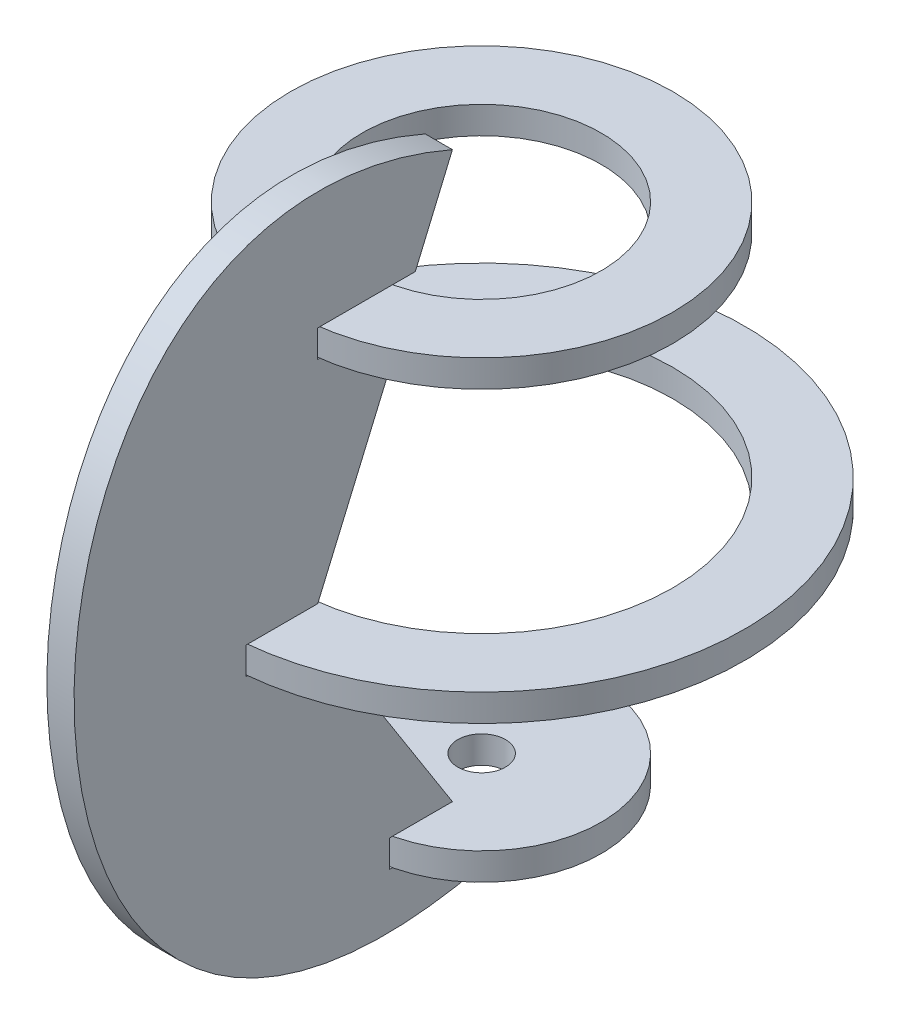
SolidWorks part; units mm, degrees
ref_plane "Piano frontale" through (0, 0, 0) normal (0, 0, 1) x (1, 0, 0)
ref_plane "Piano superiore" through (0, 0, 0) normal (0, 1, 0) x (1, 0, 0)
ref_plane "Piano destro" through (0, 0, 0) normal (1, 0, 0) x (0, 0, -1)
sketch "Schizzo2" plane through (0, 0, 0) normal (0, 1, 0) x (1, 0, 0)
  circle A0 centre (0, 0) radius 25.0225
  circle A1 centre (0, 0) radius 5
  dimension "D1" = 10
  dimension "D2" = 50.045
extrude "Estrusione-Estrusione1" add sketch "Schizzo2" along normal blind 5.7
ref_plane "Piano1" through (0, 50, 0) normal (0, 1, 0) x (1, 0, 0)
sketch "Schizzo3" plane through (0, 50, 0) normal (0, 1, 0) x (1, 0, 0)
  circle A0 centre (0, 0) radius 55.0225
  circle A1 centre (0, 0) radius 40.0225
  dimension "D1" = 110.045
  dimension "D2" = 80.045
extrude "Estrusione-Estrusione2" add sketch "Schizzo3" along normal blind 5.7 separate body
ref_plane "Piano2" through (0, 100, 0) normal (0, 1, 0) x (1, 0, 0)
sketch "Schizzo4" plane through (0, 100, 0) normal (0, 1, 0) x (1, 0, 0)
  circle A0 centre (0, 0) radius 40.0225
  circle A1 centre (0, 0) radius 25.0225
  dimension "D2" = 80.045
  dimension "D1" = 50.045
extrude "Estrusione-Estrusione3" add sketch "Schizzo4" along normal blind 5.7 separate body
sketch "Schizzo5" plane through (0, 0, 0) normal (1, 0, 0) x (0, 0, -1)
  line L0 (-5, 0) -> (-5, -8.7741)
  line L1 (-11.8183, 123.9288) -> (-19.5847, 105.7)
  line L2 (40.0225, 105.7) -> (-40.0225, 105.7) construction
  line L3 (-19.5847, 105.7) -> (-40.0225, 105.7)
  line L4 (-20.9989, 100) -> (-40.0225, 55.7)
  line L5 (55.0225, 55.7) -> (-55.0225, 55.7) construction
  line L6 (-40.0225, 105.7) -> (-40.0225, 100)
  line L7 (-40.0225, 50.0086) -> (-11.8183, 5.7)
  line L8 (25.0225, 5.7) -> (-25.0225, 5.7) construction
  line L9 (-40.0225, 100) -> (-20.9989, 100)
  line L10 (-40.0225, 55.7) -> (-55.0225, 55.7)
  line L11 (-55.0225, 55.7) -> (-55.0225, 50)
  line L12 (-55.0225, 50) -> (-40.0225, 50.0086)
  line L13 (-11.8183, 5.7) -> (-25.0225, 5.7)
  line L14 (-25.0225, 5.7) -> (-25.0225, 0)
  line L15 (-25.0225, 0) -> (-5, 0)
  spline S0 degree 3 poles (-5, -8.7741) (-122.0399, -36.7846) (-115.1307, 169.0223) (-11.8183, 123.9288) knots 0 0 0 0 1 1 1 1
extrude "Estrusione-Estrusione10" add sketch "Schizzo5" along normal blind 5.7 separate body contours S0 L1 L3 L6 L9 L4 L10 L11 L12 L7 L13 L14 L15 L0
equation "\"k\"= 0.045mm'kerf"
equation "\"w\"= 30mm'circle width"
equation "\"m\"= 5.7mm'material thickness"
equation "\"jhf\"= \"m\" - 2 * \"k\"'female joint height"
equation "\"jhm\"= \"m\" + 2 * \"k\"'male joint height"
equation "\"d\"= 50mm'circle diameter"
equation "\"d2\"= \"d\" + 30mm"
equation "\"d3\"= \"d2\" + 30mm"
equation "\"id\"= 50mm'internal circle distance"
equation "\"D2@Schizzo2\"= \"d\"+ \"k\""
equation "\"D1@Schizzo3\"= \"d3\"+ \"k\""
equation "\"D2@Schizzo3\"=\"d2\"+ \"k\""
equation "\"D1@Schizzo4\"=\"d\"+ \"k\""
equation "\"D2@Schizzo4\"=\"d2\"+ \"k\""
